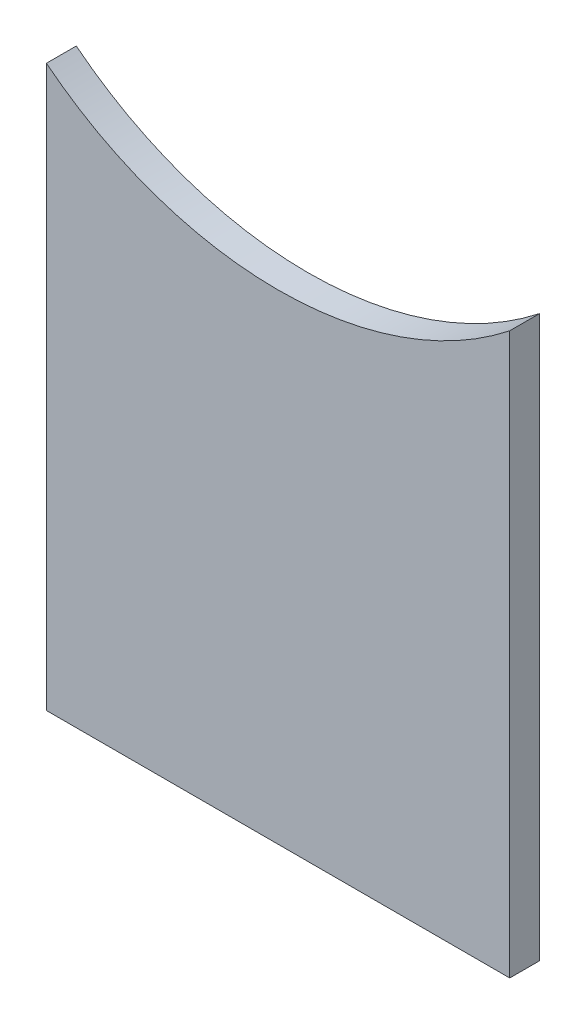
SolidWorks part; units mm, degrees
ref_plane "前视基准面" through (0, 0, 0) normal (0, 0, 1) x (1, 0, 0)
ref_plane "上视基准面" through (0, 0, 0) normal (0, 1, 0) x (1, 0, 0)
ref_plane "右视基准面" through (0, 0, 0) normal (1, 0, 0) x (0, 0, -1)
sketch "草图4" plane through (0, 0, 0) normal (0, 0, 1) x (1, 0, 0)
  line L0 (31.1831, -53.2039) -> (155.1831, -53.2039)
  line L5 (31.1831, -53.2039) -> (31.1831, 96.7961)
  line L6 (155.1831, -53.2039) -> (155.1831, 96.7961)
  line L7 (93.1831, -53.2039) -> (93.1831, 75.2563) construction
  line L8 (93.1831, 275.2563) -> (93.1831, 286.1004) construction
  arc A1 (31.1831, 96.7961) -> (155.1831, 96.7961) centre (93.1831, 175.2563) ccw
  point P5 (0, 0)
  point P7 (0, 0)
  dimension "D3" = 124
  dimension "D2" = 200
  dimension "D1" = 150
extrude "凸台-拉伸1" add sketch "草图4" along normal blind 8
